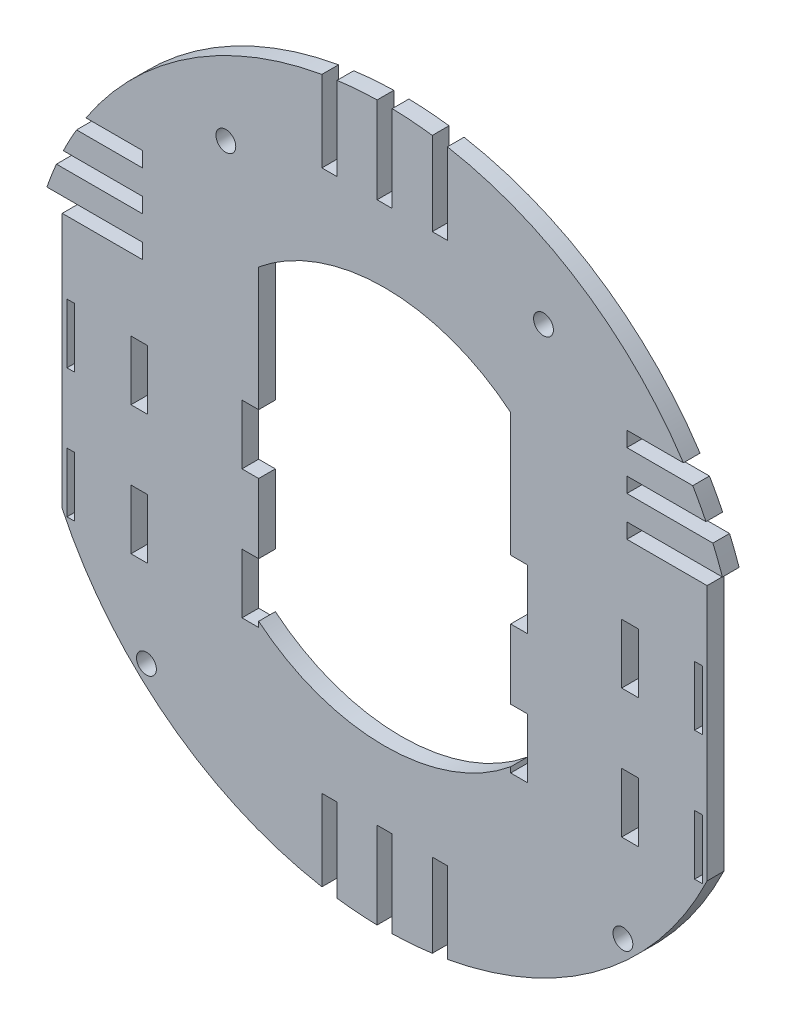
SolidWorks part; units mm, degrees
ref_plane "Front Plane" through (0, 0, 0) normal (0, 0, 1) x (1, 0, 0)
ref_plane "Top Plane" through (0, 0, 0) normal (0, 1, 0) x (1, 0, 0)
ref_plane "Right Plane" through (0, 0, 0) normal (1, 0, 0) x (0, 0, -1)
sketch "Sketch1" plane through (0, 0, 0) normal (0, 0, 1) x (1, 0, 0)
  line L2 (-40.3, 49.073) -> (-40.3, -49.073)
  line L4 (40.3, 49.073) -> (40.3, -49.073)
  circle A0 centre (0, 0) radius 114.3
  arc A1 (-40.3, -49.073) -> (40.3, -49.073) centre (0, 0) ccw
  arc A2 (40.3, 49.073) -> (-40.3, 49.073) centre (0, 0) ccw
  dimension "D1" = 228.6
  dimension "D2" = 127
extrude "Boss-Extrude1" add sketch "Sketch1" along normal blind 5.334
sketch "Sketch2" plane through (0, 0, 5.334) normal (0, 0, 1) x (1, 0, 0)
  line L0 (0, 0) -> (-50000, 0) construction
  line L1 (-20.066, 92.964) -> (-20.066, 116.3295)
  line L2 (15.24, 92.964) -> (15.24, 86.614)
  line L3 (-20.066, 116.3295) -> (-15.24, 116.3295)
  line L4 (-20.066, 92.964) -> (-20.066, 86.614)
  line L5 (-20.066, 86.614) -> (-15.24, 86.614)
  line L6 (-15.24, 92.964) -> (-15.24, 86.614)
  line L7 (-15.24, 116.3295) -> (-15.24, 92.964)
  line L8 (-2.413, 92.964) -> (-2.413, 86.614)
  line L9 (-2.413, 86.614) -> (2.413, 86.614)
  line L10 (2.413, 92.964) -> (2.413, 86.614)
  line L11 (-2.413, 92.964) -> (2.413, 86.614) construction
  line L12 (-2.413, 86.614) -> (2.413, 92.964) construction
  line L13 (20.066, 86.614) -> (15.24, 86.614)
  line L14 (20.066, 92.964) -> (20.066, 86.614)
  line L15 (-2.413, 92.964) -> (-2.413, 116.3295)
  line L16 (-2.413, 116.3295) -> (2.413, 116.3295)
  line L17 (2.413, 116.3295) -> (2.413, 92.964)
  line L18 (15.24, 92.964) -> (15.24, 116.3295)
  line L19 (15.24, 116.3295) -> (20.066, 116.3295)
  line L20 (20.066, 116.3295) -> (20.066, 92.964)
  line L21 (-2.413, -86.614) -> (2.413, -92.964) construction
  line L22 (-2.413, -92.964) -> (2.413, -86.614) construction
  line L23 (20.066, -116.3295) -> (20.066, -92.964)
  line L24 (15.24, -116.3295) -> (20.066, -116.3295)
  line L25 (15.24, -92.964) -> (15.24, -116.3295)
  line L26 (2.413, -116.3295) -> (2.413, -92.964)
  line L27 (-2.413, -116.3295) -> (2.413, -116.3295)
  line L28 (-2.413, -92.964) -> (-2.413, -116.3295)
  line L29 (20.066, -92.964) -> (20.066, -86.614)
  line L30 (20.066, -86.614) -> (15.24, -86.614)
  line L31 (2.413, -92.964) -> (2.413, -86.614)
  line L32 (-2.413, -86.614) -> (2.413, -86.614)
  line L33 (-2.413, -92.964) -> (-2.413, -86.614)
  line L34 (-15.24, -116.3295) -> (-15.24, -92.964)
  line L35 (-15.24, -92.964) -> (-15.24, -86.614)
  line L36 (-20.066, -86.614) -> (-15.24, -86.614)
  line L37 (-20.066, -92.964) -> (-20.066, -86.614)
  line L38 (-20.066, -116.3295) -> (-15.24, -116.3295)
  line L39 (15.24, -92.964) -> (15.24, -86.614)
  line L40 (-20.066, -92.964) -> (-20.066, -116.3295)
  point P9 (0, 89.789)
  point P40 (0, -89.789)
  dimension "D1" = 86.614
  dimension "D5" = 6.35
extrude "TopBottomCuts" cut sketch "Sketch2" against normal through all
sketch "Sketch3" plane through (0, 0, 5.334) normal (0, 0, 1) x (1, 0, 0)
  line L0 (0, 0) -> (0, 50000) construction
  line L1 (-83.82, 37.338) -> (-77.47, 37.338)
  line L2 (-83.82, 62.738) -> (-104.1636, 62.738)
  line L3 (-83.82, 32.512) -> (-77.47, 32.512)
  line L4 (-77.47, 37.338) -> (-77.47, 32.512)
  line L5 (0, 0) -> (-50000, 0) construction
  line L6 (-83.82, 50.038) -> (-77.47, 50.038)
  line L7 (-104.1636, 62.738) -> (-104.1636, 57.912)
  line L8 (-83.82, 45.212) -> (-77.47, 45.212)
  line L9 (-77.47, 50.038) -> (-77.47, 45.212)
  line L10 (-83.82, 62.738) -> (-77.47, 62.738)
  line L11 (-104.1636, 57.912) -> (-83.82, 57.912)
  line L12 (-83.82, 57.912) -> (-77.47, 57.912)
  line L13 (-77.47, 62.738) -> (-77.47, 57.912)
  line L14 (-83.82, 50.038) -> (-108.2966, 50.038)
  line L15 (-108.2966, 50.038) -> (-108.2966, 45.212)
  line L16 (-108.2966, 45.212) -> (-83.82, 45.212)
  line L17 (-83.82, 37.338) -> (-110.9479, 37.338)
  line L18 (-110.9479, 37.338) -> (-110.9479, 32.512)
  line L19 (-110.9479, 32.512) -> (-83.82, 32.512)
  line L20 (-83.82, 82.3848) -> (-83.82, 13.9755) construction
  line L21 (110.9479, 32.512) -> (83.82, 32.512)
  line L22 (110.9479, 37.338) -> (110.9479, 32.512)
  line L23 (83.82, 37.338) -> (110.9479, 37.338)
  line L24 (108.2966, 45.212) -> (83.82, 45.212)
  line L25 (108.2966, 50.038) -> (108.2966, 45.212)
  line L26 (83.82, 50.038) -> (108.2966, 50.038)
  line L27 (77.47, 62.738) -> (77.47, 57.912)
  line L28 (83.82, 57.912) -> (77.47, 57.912)
  line L29 (104.1636, 57.912) -> (83.82, 57.912)
  line L30 (83.82, 62.738) -> (77.47, 62.738)
  line L31 (77.47, 50.038) -> (77.47, 45.212)
  line L32 (83.82, 45.212) -> (77.47, 45.212)
  line L33 (104.1636, 62.738) -> (104.1636, 57.912)
  line L34 (83.82, 50.038) -> (77.47, 50.038)
  line L35 (77.47, 37.338) -> (77.47, 32.512)
  line L36 (83.82, 32.512) -> (77.47, 32.512)
  line L37 (83.82, 62.738) -> (104.1636, 62.738)
  line L38 (83.82, 37.338) -> (77.47, 37.338)
  dimension "D1" = 6.35
  dimension "D2" = 4.826
  dimension "D3" = 77.47
  dimension "D4" = 32.512
  dimension "D6" = 7.874
  dimension "D5" = 3
extrude "SideCuts" cut sketch "Sketch3" against normal through all
sketch "Sketch4" plane through (0, 0, 5.334) normal (0, 0, 1) x (1, 0, 0)
  line L0 (0, 0) -> (-50000, 0) construction
  line L1 (0, 0) -> (0, 50000) construction
  line L2 (-101.6, -31.75) -> (-99.1362, -31.75)
  line L3 (-101.6, 9.525) -> (-99.1362, 9.525)
  line L4 (-101.6, 9.525) -> (-101.6, -9.525)
  line L5 (-101.6, -9.525) -> (-99.1362, -9.525)
  line L6 (-99.1362, 9.525) -> (-99.1362, -9.525)
  line L7 (-101.6, 9.525) -> (-99.1362, -9.525) construction
  line L8 (-101.6, -9.525) -> (-99.1362, 9.525) construction
  line L9 (-81.1362, 9.525) -> (-75.8022, 9.525)
  line L10 (-81.1362, 9.525) -> (-81.1362, -9.525)
  line L11 (-81.1362, -9.525) -> (-75.8022, -9.525)
  line L12 (-75.8022, 9.525) -> (-75.8022, -9.525)
  line L13 (-81.1362, 9.525) -> (-75.8022, -9.525) construction
  line L14 (-81.1362, -9.525) -> (-75.8022, 9.525) construction
  line L15 (-45.634, 9.525) -> (-40.3, 9.525)
  line L16 (-45.634, 9.525) -> (-45.634, -9.525)
  line L17 (-45.634, -9.525) -> (-40.3, -9.525)
  line L18 (-40.3, 9.525) -> (-40.3, -9.525)
  line L19 (-45.634, 9.525) -> (-40.3, -9.525) construction
  line L20 (-45.634, -9.525) -> (-40.3, 9.525) construction
  line L21 (-101.6, -31.75) -> (-101.6, -50.8)
  line L22 (-101.6, -50.8) -> (-99.1362, -50.8)
  line L23 (-99.1362, -31.75) -> (-99.1362, -50.8)
  line L24 (-81.1362, -31.75) -> (-75.8022, -31.75)
  line L25 (-81.1362, -31.75) -> (-81.1362, -50.8)
  line L26 (-81.1362, -50.8) -> (-75.8022, -50.8)
  line L27 (-75.8022, -31.75) -> (-75.8022, -50.8)
  line L28 (-45.634, -31.75) -> (-40.3, -31.75)
  line L29 (-45.634, -31.75) -> (-45.634, -50.8)
  line L30 (-45.634, -50.8) -> (-40.3, -50.8)
  line L31 (-40.3, -31.75) -> (-40.3, -50.8)
  line L32 (-101.6, -31.75) -> (-99.1362, -50.8) construction
  line L33 (-101.6, -50.8) -> (-99.1362, -31.75) construction
  line L34 (-81.1362, -31.75) -> (-75.8022, -50.8) construction
  line L35 (-81.1362, -50.8) -> (-75.8022, -31.75) construction
  line L36 (-45.634, -31.75) -> (-40.3, -50.8) construction
  line L37 (-45.634, -50.8) -> (-40.3, -31.75) construction
  line L38 (45.634, -50.8) -> (40.3, -31.75) construction
  line L39 (45.634, -31.75) -> (40.3, -50.8) construction
  line L40 (81.1362, -50.8) -> (75.8022, -31.75) construction
  line L41 (81.1362, -31.75) -> (75.8022, -50.8) construction
  line L42 (101.6, -50.8) -> (99.1362, -31.75) construction
  line L43 (101.6, -31.75) -> (99.1362, -50.8) construction
  line L44 (45.634, -9.525) -> (40.3, 9.525) construction
  line L45 (45.634, 9.525) -> (40.3, -9.525) construction
  line L46 (81.1362, -9.525) -> (75.8022, 9.525) construction
  line L47 (81.1362, 9.525) -> (75.8022, -9.525) construction
  line L48 (101.6, -9.525) -> (99.1362, 9.525) construction
  line L49 (101.6, 9.525) -> (99.1362, -9.525) construction
  line L50 (0, 0) -> (50000, 0) construction
  line L51 (40.3, -31.75) -> (40.3, -50.8)
  line L52 (45.634, -50.8) -> (40.3, -50.8)
  line L53 (45.634, -31.75) -> (45.634, -50.8)
  line L54 (45.634, -31.75) -> (40.3, -31.75)
  line L55 (75.8022, -31.75) -> (75.8022, -50.8)
  line L56 (81.1362, -50.8) -> (75.8022, -50.8)
  line L57 (81.1362, -31.75) -> (81.1362, -50.8)
  line L58 (81.1362, -31.75) -> (75.8022, -31.75)
  line L59 (99.1362, -31.75) -> (99.1362, -50.8)
  line L60 (101.6, -50.8) -> (99.1362, -50.8)
  line L61 (101.6, -31.75) -> (101.6, -50.8)
  line L62 (40.3, 9.525) -> (40.3, -9.525)
  line L63 (45.634, -9.525) -> (40.3, -9.525)
  line L64 (45.634, 9.525) -> (45.634, -9.525)
  line L65 (45.634, 9.525) -> (40.3, 9.525)
  line L66 (75.8022, 9.525) -> (75.8022, -9.525)
  line L67 (81.1362, -9.525) -> (75.8022, -9.525)
  line L68 (81.1362, 9.525) -> (81.1362, -9.525)
  line L69 (81.1362, 9.525) -> (75.8022, 9.525)
  line L70 (99.1362, 9.525) -> (99.1362, -9.525)
  line L71 (101.6, -9.525) -> (99.1362, -9.525)
  line L72 (101.6, 9.525) -> (101.6, -9.525)
  line L73 (101.6, 9.525) -> (99.1362, 9.525)
  line L74 (101.6, -31.75) -> (99.1362, -31.75)
  point P5 (-100.3681, 0)
  point P10 (-78.4692, 0)
  point P15 (-42.967, 0)
  point P20 (-100.3681, -41.275)
  point P26 (-78.4692, -41.275)
  point P31 (-42.967, -41.275)
  point P61 (42.967, -41.275)
  point P62 (78.4692, -41.275)
  point P63 (100.3681, -41.275)
  point P64 (42.967, 0)
  point P65 (78.4692, 0)
  point P66 (100.3681, 0)
  dimension "D1" = 99.1362
  dimension "D2" = 2.4638
  dimension "D3" = 19.05
  dimension "D4" = 75.8022
  dimension "D5" = 40.3
  dimension "D6" = 5.334
  dimension "D7" = 5.334
  dimension "D9" = 22.225
  dimension "D10" = 19.05
  dimension "D11" = 19.05
  dimension "D8" = 2
extrude "MotorMounts" cut sketch "Sketch4" against normal through all
sketch "Sketch5" plane through (0, 0, 5.334) normal (0, 0, 1) x (1, 0, 0)
  line L0 (0, 0) -> (50000, 0) construction
  line L1 (0, 0) -> (0, 50000) construction
  circle A0 centre (-76.2, -78.74) radius 3.175
  circle A1 centre (-50.8, 78.74) radius 3.175
  circle A2 centre (76.2, -78.74) radius 3.175
  circle A3 centre (50.8, 78.74) radius 3.175
  dimension "D1" = 6.35
  dimension "D2" = 6.35
  dimension "D3" = 76.2
  dimension "D4" = 78.74
  dimension "D5" = 78.74
  dimension "D6" = 50.8
extrude "BoltHoles" cut sketch "Sketch5" against normal through all
sketch "Sketch6" plane through (0, 0, 5.334) normal (0, 0, 1) x (1, 0, 0)
  line L0 (0, 0) -> (0, -50000) construction
  line L1 (0, 0) -> (50000, 0) construction
  line L2 (-103.124, 34.176) -> (-125.476, 34.176)
  line L3 (125.476, -49.2943) -> (106.5516, 34.176) construction
  line L4 (-125.476, 34.176) -> (-125.476, -49.2943)
  line L5 (-125.476, -49.2943) -> (-103.124, -49.2943)
  line L6 (-103.124, 34.176) -> (-103.124, -49.2943)
  line L7 (-122.0484, 34.176) -> (-103.124, -49.2943) construction
  line L8 (-125.476, -49.2943) -> (-106.5516, 34.176) construction
  line L9 (122.0484, 34.176) -> (103.124, -49.2943) construction
  line L10 (103.124, 34.176) -> (103.124, -49.2943)
  line L11 (125.476, -49.2943) -> (103.124, -49.2943)
  line L12 (125.476, 34.176) -> (125.476, -49.2943)
  line L13 (103.124, 34.176) -> (125.476, 34.176)
  arc A0 (-109.5786, 32.512) -> (-20.066, -112.5249) centre (0, 0) ccw construction
  point P5 (-114.3, 0)
  point P22 (114.3, 0)
  dimension "D1" = 1.524
extrude "Wheel Cutouts" cut sketch "Sketch6" against normal through all
